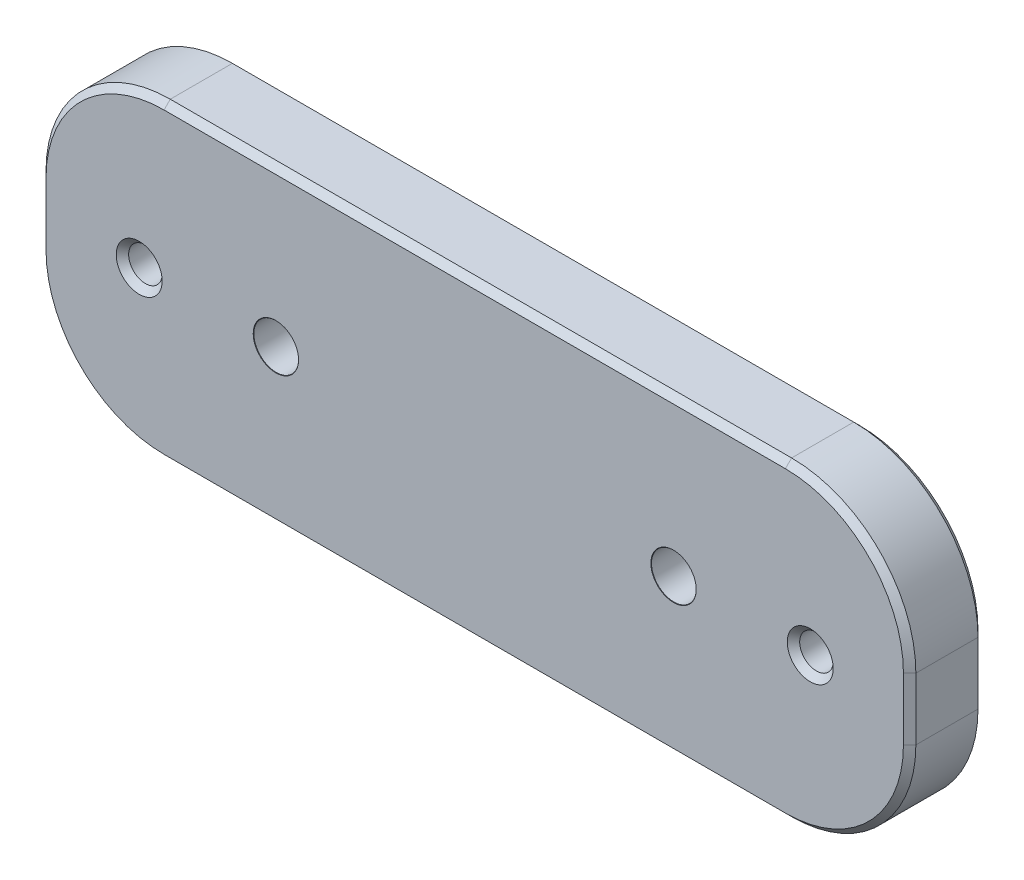
SolidWorks part; units mm, degrees
material "ABS"
ref_plane "Front Plane" through (0, 0, 0) normal (0, 0, 1) x (1, 0, 0)
ref_plane "Top Plane" through (0, 0, 0) normal (0, 1, 0) x (1, 0, 0)
ref_plane "Right Plane" through (0, 0, 0) normal (1, 0, 0) x (0, 0, -1)
sketch "Sketch1" plane through (0, 0, 0) normal (0, 0, 1) x (1, 0, 0)
  line L1 (-35, 12.5) -> (35, 12.5)
  line L2 (-35, 12.5) -> (-35, -12.5)
  line L3 (-35, -12.5) -> (35, -12.5)
  line L4 (35, 12.5) -> (35, -12.5)
  line L5 (-35, 12.5) -> (35, -12.5) construction
  line L6 (-35, -12.5) -> (35, 12.5) construction
  circle A0 centre (-27, 0) radius 1.35
  circle A1 centre (27, 0) radius 1.35
  circle A2 centre (-16, 0) radius 1.35
  circle A3 centre (16, 0) radius 1.35
  point P0 (0, 0)
  dimension "D5" = 2.7
  dimension "D1" = 70
  dimension "D2" = 25
  dimension "D3" = 27
  dimension "D4" = 27
  dimension "D6" = 11
  dimension "D7" = 11
extrude "Boss-Extrude1" add sketch "Sketch1" along normal blind 6
chamfer "Chamfer1" distance 0.5 angle 45 4 edges at (28.35, 0, 6) (-25.65, 0, 6) (28.35, 0, 0) (-25.65, 0, 0)
fillet "Fillet1" radius 10 4 edges at (-35, -12.5, 3) (35, -12.5, 3) (-35, 12.5, 3) (35, 12.5, 3)
chamfer "Chamfer2" distance 0.5 angle 45 16 edges at (-35, 0, 6) (-35, 0, 0) (-32.0711, -9.5711, 6) (-32.0711, -9.5711, 0) (0, -12.5, 6) (0, -12.5, 0) (32.0711, -9.5711, 6) (32.0711, -9.5711, 0) (0, 12.5, 6) (35, 0, 6) (0, 12.5, 0) (35, 0, 0) (-32.0711, 9.5711, 6) (32.0711, 9.5711, 6) (-32.0711, 9.5711, 0) (32.0711, 9.5711, 0)
hole_wizard "CSK for M3 Countersunk Flat Head Screw1" positions "Sketch2" profile "Sketch3" countersink size "M3" standard "ISO" end condition up to next
sketch "Sketch2" plane through (0, 0, 0) normal (0, 0, -1) x (-1, 0, 0)
  point P0 (16, 0)
  point P3 (-16, 0)
sketch "Sketch3" plane through (-16, 0, 0) normal (1, 0, 0) x (0, 1, 0)
  line L0 (0, 0) -> (0, 6)
  line L1 (0, 6) -> (1.825, 6)
  line L2 (1.8, 5.975) -> (1.8, 2.35)
  line L3 (1.8, 2.35) -> (4.15, 0)
  line L5 (4.15, 0) -> (0, 0)
  line L6 (-1.8, 2.35) -> (-4.15, 0) construction
  line L7 (1.825, 6) -> (1.8, 5.975)
  line L8 (-1.825, 6) -> (-1.8, 5.975) construction
  line L11 (0, -6.35) -> (0, 107.95) construction
  dimension "Thru Hole Dia." = 3.6
  dimension "Thru Hole Depth" = 6
  dimension "Near C'Sink Dia." = 8.3
  dimension "Near C'Sink Angle" = 90
  dimension "Far C'Sink Dia." = 3.65
  dimension "Far C'Sink Angle" = 90
equation "\"D4@Sketch1\"=\"D3@Sketch1\""
